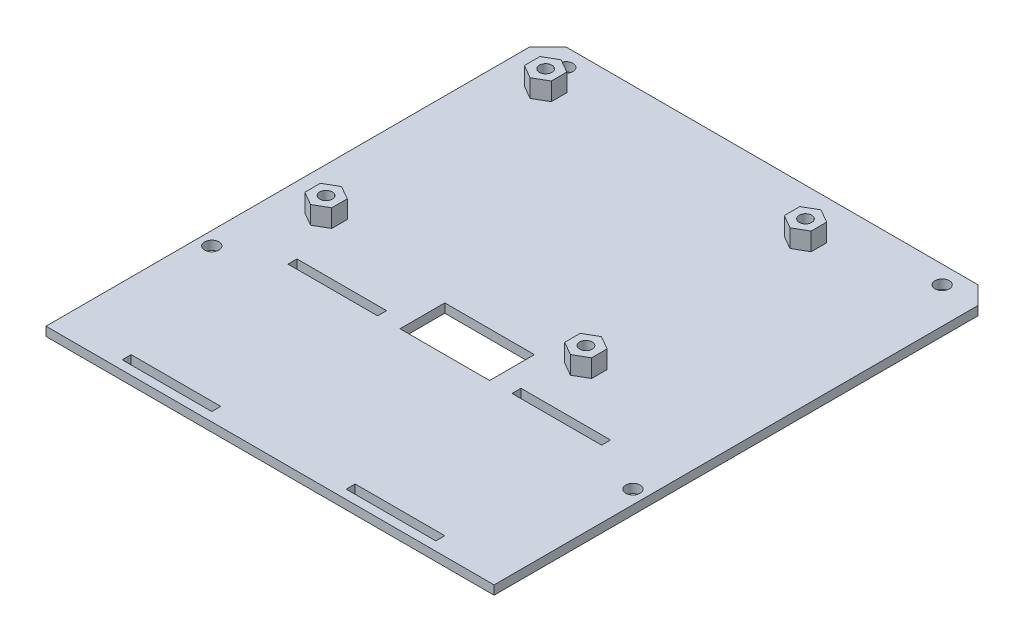
SolidWorks part; units mm, degrees
ref_plane "Front Plane" through (0, 0, 0) normal (0, 0, 1) x (1, 0, 0)
ref_plane "Top Plane" through (0, 0, 0) normal (0, 1, 0) x (1, 0, 0)
ref_plane "Right Plane" through (0, 0, 0) normal (1, 0, 0) x (0, 0, -1)
sketch "Sketch1" plane through (0, 0, 0) normal (0, 1, 0) x (1, 0, 0)
  line L1 (0, 0) -> (100, 0)
  line L2 (0, 0) -> (0, 82)
  line L3 (0, 82) -> (100, 82)
  line L4 (100, 0) -> (100, 82)
  dimension "D1" = 100
  dimension "D2" = 82
extrude "Boss-Extrude1" add sketch "Sketch1" along normal blind 2
chamfer "Chamfer1" distance 4 angle 45 2 edges at (100, 1, -82) (0, 1, -82)
sketch "Sketch2" plane through (0, 2, 0) normal (0, 1, 0) x (1, 0, 0)
  line L0 (0, 78) -> (0, 0) construction
  line L1 (100, 0) -> (100, 78) construction
  line L2 (0, 0) -> (100, 0) construction
  circle A0 centre (8, 78) radius 1.6
  circle A1 centre (92, 78) radius 1.6
  circle A2 centre (97, 4) radius 1.6
  circle A3 centre (3, 4) radius 1.6
  dimension "D9" = 3.2
  dimension "D10" = 3.2
  dimension "D11" = 3.2
  dimension "D12" = 3.2
  dimension "D1" = 4
  dimension "D2" = 4
  dimension "D3" = 4
  dimension "D4" = 4
  dimension "D5" = 4
  dimension "D6" = 3
  dimension "D7" = 3
  dimension "D8" = 4
extrude "Cut-Extrude1" cut sketch "Sketch2" against normal through all
sketch "Sketch3" plane through (0, 0, 0) normal (0, 0, 1) x (1, 0, 0)
  line L1 (0, 2) -> (100, 2)
  line L2 (0, 2) -> (0, 0)
  line L3 (0, 0) -> (100, 0)
  line L4 (100, 2) -> (100, 0)
extrude "Boss-Extrude2" add sketch "Sketch3" along normal blind 30
sketch "Sketch4" plane through (0, 2, 0) normal (0, 1, 0) x (1, 0, 0)
  line L0 (0, 78) -> (0, -30) construction
  line L1 (15, -26) -> (35, -26)
  line L2 (15, -26) -> (15, -28)
  line L3 (15, -28) -> (35, -28)
  line L4 (35, -26) -> (35, -28)
  line L5 (65, -26) -> (85, -26)
  line L6 (65, -26) -> (65, -28)
  line L7 (65, -28) -> (85, -28)
  line L8 (85, -26) -> (85, -28)
  line L9 (15, 11) -> (35, 11)
  line L10 (15, 11) -> (15, 9)
  line L11 (15, 9) -> (35, 9)
  line L12 (35, 11) -> (35, 9)
  line L13 (65, 11) -> (85, 11)
  line L14 (65, 11) -> (65, 9)
  line L15 (65, 9) -> (85, 9)
  line L16 (85, 11) -> (85, 9)
  line L17 (100, -30) -> (100, 78) construction
  line L18 (100, -30) -> (0, -30) construction
  dimension "D1" = 20
  dimension "D2" = 20
  dimension "D3" = 20
  dimension "D4" = 20
  dimension "D5" = 15
  dimension "D6" = 15
  dimension "D7" = 2
  dimension "D8" = 2
  dimension "D9" = 2
  dimension "D10" = 2
  dimension "D11" = 15
  dimension "D12" = 15
  dimension "D13" = 2
  dimension "D14" = 35
  dimension "D15" = 35
  dimension "D16" = 2
extrude "Cut-Extrude2" cut sketch "Sketch4" against normal through all
sketch "Sketch5" plane through (0, 2, 0) normal (0, 1, 0) x (1, 0, 0)
  line L0 (96, 82) -> (4, 82) construction
  line L1 (10, 71.5) -> (68, 71.5)
  line L2 (10, 71.5) -> (10, 22.5)
  line L3 (10, 22.5) -> (68, 22.5)
  line L4 (68, 71.5) -> (68, 22.5)
  line L5 (10, 68.0359) -> (13, 69.7679)
  line L6 (13, 69.7679) -> (13, 73.2321)
  line L7 (13, 73.2321) -> (10, 74.9641)
  line L8 (10, 74.9641) -> (7, 73.2321)
  line L9 (7, 73.2321) -> (7, 69.7679)
  line L10 (7, 69.7679) -> (10, 68.0359)
  line L11 (10, 25.9641) -> (7, 24.2321)
  line L12 (7, 24.2321) -> (7, 20.7679)
  line L13 (7, 20.7679) -> (10, 19.0359)
  line L14 (10, 19.0359) -> (13, 20.7679)
  line L15 (13, 20.7679) -> (13, 24.2321)
  line L16 (13, 24.2321) -> (10, 25.9641)
  line L17 (68, 25.9641) -> (65, 24.2321)
  line L18 (65, 24.2321) -> (65, 20.7679)
  line L19 (65, 20.7679) -> (68, 19.0359)
  line L20 (68, 19.0359) -> (71, 20.7679)
  line L21 (71, 20.7679) -> (71, 24.2321)
  line L22 (71, 24.2321) -> (68, 25.9641)
  line L23 (68, 68.0359) -> (71, 69.7679)
  line L24 (71, 69.7679) -> (71, 73.2321)
  line L25 (71, 73.2321) -> (68, 74.9641)
  line L26 (68, 74.9641) -> (65, 73.2321)
  line L27 (65, 73.2321) -> (65, 69.7679)
  line L28 (65, 69.7679) -> (68, 68.0359)
  line L29 (0, 78) -> (0, -30) construction
  circle A0 centre (10, 71.5) radius 3 construction
  circle A1 centre (10, 22.5) radius 3 construction
  circle A2 centre (68, 22.5) radius 3 construction
  circle A3 centre (68, 71.5) radius 3 construction
  dimension "D3" = 6
  dimension "D4" = 6
  dimension "D5" = 6
  dimension "D6" = 6
  dimension "D1" = 49
  dimension "D2" = 58
  dimension "D7" = 10.5
  dimension "D8" = 10
extrude "Boss-Extrude3" add sketch "Sketch5" along normal blind 4 contours L24 L25 L26 L27 L28 L23 | L21 L22 L17 L18 L19 L20 | L10 L5 L6 L7 L8 L9 | L14 L15 L16 L11 L12 L13
sketch "Sketch6" plane through (0, 6, 0) normal (0, 1, 0) x (1, 0, 0)
  line L0 (7, 73.2321) -> (13, 69.7679) construction
  line L1 (13, 69.7679) -> (65, 69.7679) construction
  line L2 (65, 69.7679) -> (71, 73.2321) construction
  line L3 (71, 69.7679) -> (71, 73.2321) construction
  line L4 (71, 73.2321) -> (71, 24.2321) construction
  line L5 (71, 24.2321) -> (65, 20.7679) construction
  line L6 (65, 20.7679) -> (13, 24.2321) construction
  line L7 (13, 24.2321) -> (7, 20.7679) construction
  circle A0 centre (10, 71.5) radius 1.4
  circle A1 centre (68, 71.5) radius 1.4
  circle A2 centre (68, 22.5) radius 1.4
  circle A3 centre (10, 22.5) radius 1.4
  dimension "D1" = 2.8
  dimension "D2" = 2.8
  dimension "D3" = 2.8
  dimension "D4" = 2.8
extrude "Cut-Extrude3" cut sketch "Sketch6" against normal through all
sketch "Sketch7" plane through (0, 2, 0) normal (0, 1, 0) x (1, 0, 0)
  line L0 (50, 82) -> (50, -30) construction
  line L1 (96, 82) -> (4, 82) construction
  line L2 (100, -30) -> (0, -30) construction
  line L3 (15, 9) -> (35, 9) construction
  line L4 (40, 19) -> (60, 19)
  line L5 (40, 19) -> (40, 9)
  line L6 (40, 9) -> (60, 9)
  line L7 (60, 19) -> (60, 9)
  dimension "D1" = 20
  dimension "D2" = 10
  dimension "D3" = 0
  dimension "D4" = 10
extrude "Cut-Extrude4" cut sketch "Sketch7" against normal through all
